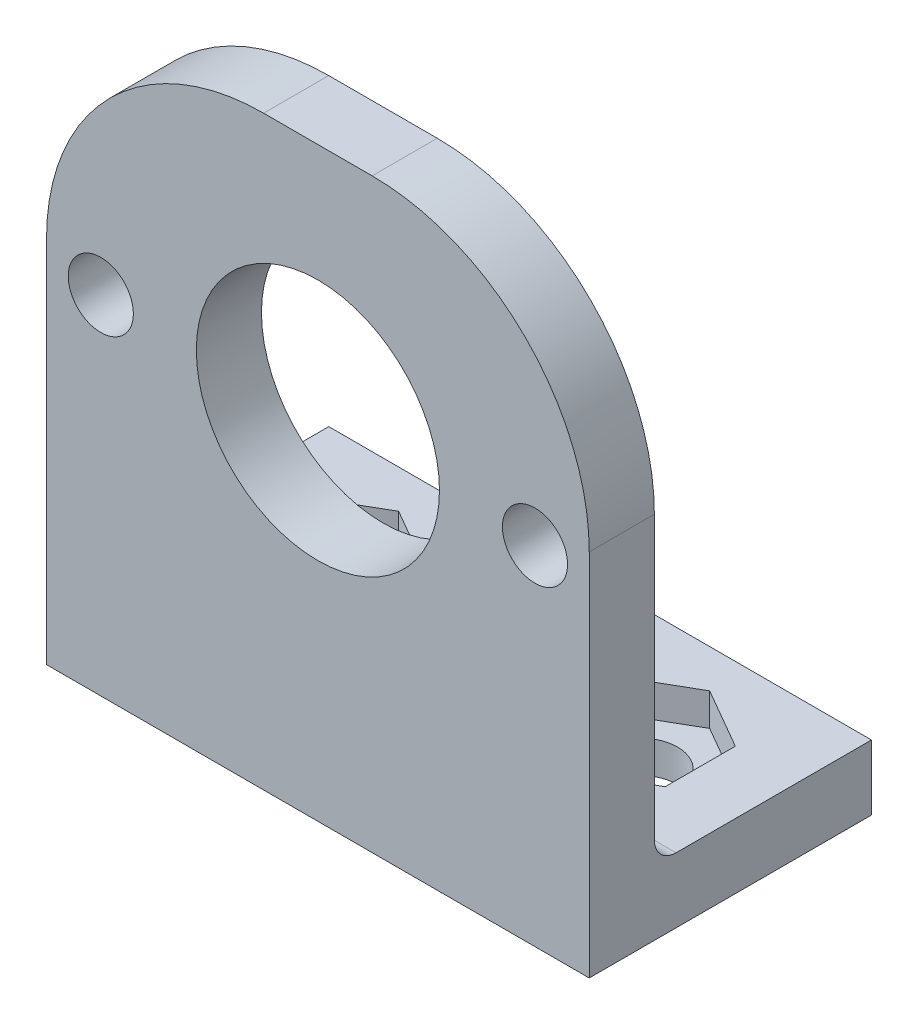
SolidWorks part; units mm, degrees
ref_plane "Спереди" through (0, 0, 0) normal (0, 0, 1) x (1, 0, 0)
ref_plane "Сверху" through (0, 0, 0) normal (0, 1, 0) x (1, 0, 0)
ref_plane "Справа" through (0, 0, 0) normal (1, 0, 0) x (0, 0, -1)
sketch "Эскиз1" plane through (0, 0, 0) normal (0, 0, 1) x (1, 0, 0)
  line L1 (-12.5, 13.5) -> (12.5, 13.5)
  line L2 (-12.5, 13.5) -> (-12.5, -13.5)
  line L3 (-12.5, -13.5) -> (12.5, -13.5)
  line L4 (12.5, 13.5) -> (12.5, -13.5)
  line L5 (-12.5, 13.5) -> (12.5, -13.5) construction
  line L6 (-12.5, -13.5) -> (12.5, 13.5) construction
  point P0 (0, 0)
  dimension "D1" = 25
  dimension "D2" = 27
extrude "Бобышка-Вытянуть1" add sketch "Эскиз1" along normal blind 3
sketch "Эскиз2" plane through (0, 0, 0) normal (0, 0, -1) x (-1, 0, 0)
  line L0 (12.5, 13.5) -> (12.5, -13.5) construction
  line L1 (-12.5, -13.5) -> (12.5, -13.5)
  line L2 (-12.5, -13.5) -> (-12.5, -10.504)
  line L3 (-12.5, -10.504) -> (12.5, -10.504)
  line L4 (12.5, -13.5) -> (12.5, -10.504)
extrude "Бобышка-Вытянуть2" add sketch "Эскиз2" along normal blind 10
sketch "Эскиз3" plane through (0, 0, 3) normal (0, 0, 1) x (1, 0, 0)
  circle A0 centre (0, 2.5) radius 5.6
  dimension "D1" = 16
extrude "Вырез-Вытянуть1" cut sketch "Эскиз3" against normal blind 10
fillet "Скругление1" radius 10 2 edges at (12.5, 13.5, 1.5) (-12.5, 13.5, 1.5)
sketch "Эскиз4" plane through (0, -13.5, 0) normal (0, -1, 0) x (1, 0, 0)
  line L0 (0, 0) -> (0, -12.7649) construction
  line L1 (-17.0078, -5) -> (16.5246, -5) construction
  circle A0 centre (-7.5134, -5) radius 1.75
  circle A1 centre (6.8128, -5) radius 1.75
  dimension "D1" = 5
extrude "Вырез-Вытянуть2" cut sketch "Эскиз4" against normal blind 10
fillet "Скругление2" radius 1 1 edges at (0, -10.504, 0)
sketch "Эскиз5" plane through (0, -10.504, 0) normal (0, 1, 0) x (1, 0, 0)
  line L0 (-10.6631, 5) -> (2.4892, 5) construction
  line L1 (9.6128, 3.3834) -> (9.6128, 6.6166)
  line L2 (9.6128, 6.6166) -> (6.8128, 8.2332)
  line L3 (6.8128, 8.2332) -> (4.0128, 6.6166)
  line L4 (4.0128, 6.6166) -> (4.0128, 3.3834)
  line L5 (4.0128, 3.3834) -> (6.8128, 1.7668)
  line L6 (6.8128, 1.7668) -> (9.6128, 3.3834)
  line L9 (-4.7134, 3.3834) -> (-4.7134, 6.6166)
  line L10 (-4.7134, 6.6166) -> (-7.5134, 8.2332)
  line L11 (-7.5134, 8.2332) -> (-10.3134, 6.6166)
  line L12 (-10.3134, 6.6166) -> (-10.3134, 3.3834)
  line L13 (-10.3134, 3.3834) -> (-7.5134, 1.7668)
  line L14 (-7.5134, 1.7668) -> (-4.7134, 3.3834)
  circle A0 centre (6.8128, 5) radius 2.8 construction
  circle A2 centre (-7.5134, 5) radius 2.8 construction
  dimension "D1" = 5.6
extrude "Вырез-Вытянуть3" cut sketch "Эскиз5" against normal blind 1.5
sketch "Эскиз6" plane through (0, 0, 3) normal (0, 0, 1) x (1, 0, 0)
  line L0 (-16.5157, 2.5) -> (22.6375, 2.5) construction
  circle A0 centre (-10, 2.5) radius 1.5
  circle A1 centre (10, 2.5) radius 1.5
extrude "Вырез-Вытянуть10" cut sketch "Эскиз6" against normal through all
